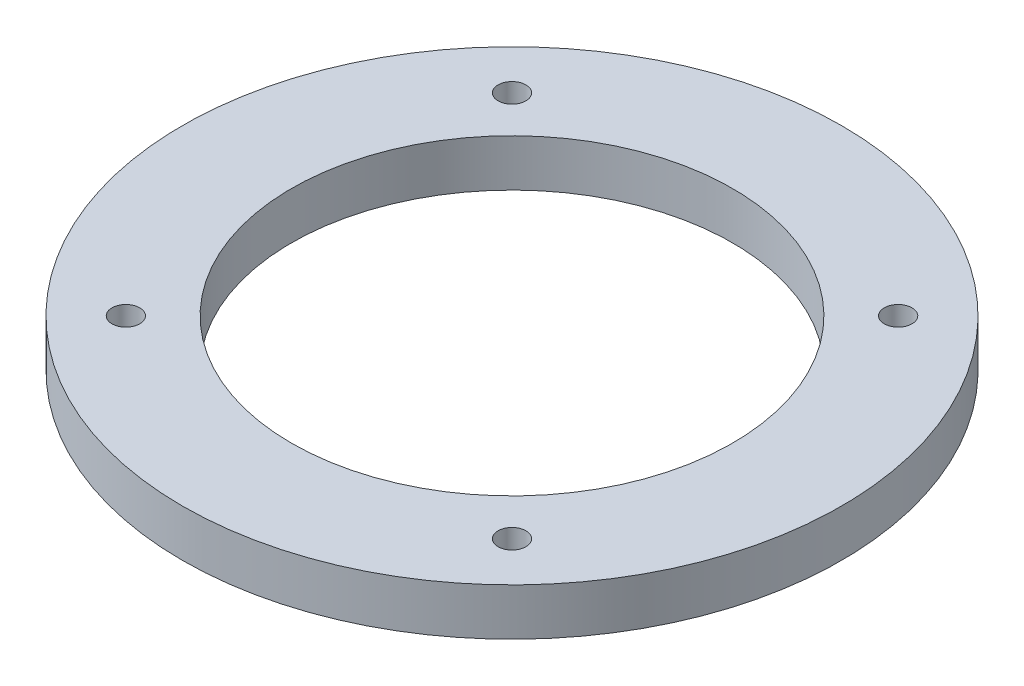
SolidWorks part; units mm, degrees
ref_plane "Front Plane" through (0, 0, 0) normal (0, 0, 1) x (1, 0, 0)
ref_plane "Top Plane" through (0, 0, 0) normal (0, 1, 0) x (1, 0, 0)
ref_plane "Right Plane" through (0, 0, 0) normal (1, 0, 0) x (0, 0, -1)
sketch "Sketch1" plane through (0, 0, 0) normal (0, 1, 0) x (1, 0, 0)
  line L0 (0, 35) -> (0, -35) construction
  line L1 (-35, 0) -> (35, 0) construction
  circle A0 centre (0, 0) radius 23.425
  circle A1 centre (0, 0) radius 35
  circle A2 centre (-20.505, 20.505) radius 1.475
  circle A3 centre (20.505, 20.505) radius 1.475
  circle A4 centre (20.505, -20.505) radius 1.475
  circle A5 centre (-20.505, -20.505) radius 1.475
  dimension "D1" = 46.85
  dimension "D2" = 70
  dimension "D3" = 2.95
  dimension "D4" = 41.01
  dimension "D5" = 41.01
extrude "Boss-Extrude1" add sketch "Sketch1" along normal mid plane 5
